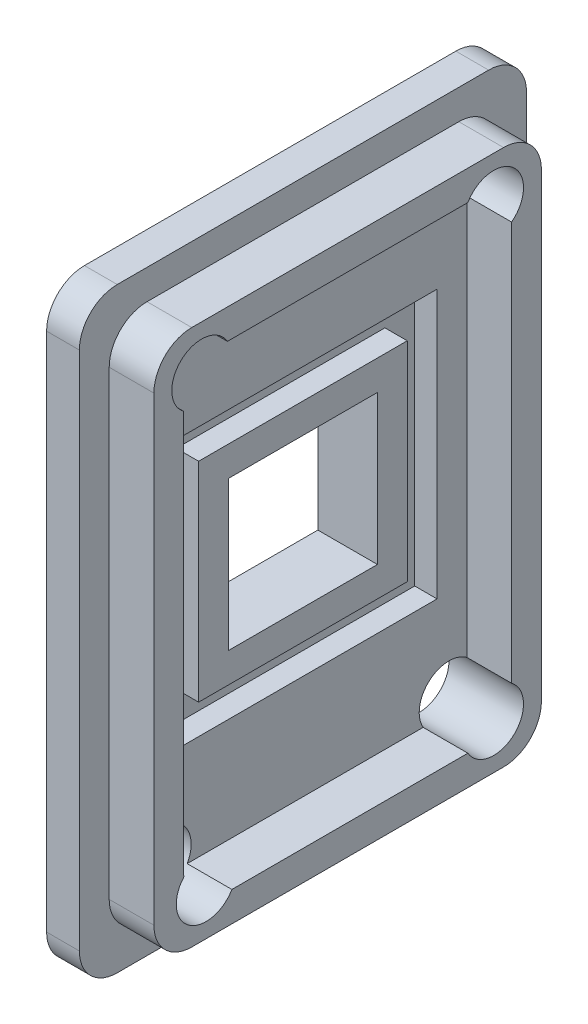
SolidWorks part; units mm, degrees
ref_plane "Front Plane" through (0, 0, 0) normal (0, 0, 1) x (1, 0, 0)
ref_plane "Top Plane" through (0, 0, 0) normal (0, 1, 0) x (1, 0, 0)
ref_plane "Right Plane" through (0, 0, 0) normal (1, 0, 0) x (0, 0, -1)
sketch "Sketch2" plane through (0, 0, 0) normal (1, 0, 0) x (0, 0, -1)
  line L1 (2.54, 0) -> (27.46, 0)
  line L2 (0, 2.54) -> (0, 37.46)
  line L3 (2.54, 40) -> (27.46, 40)
  line L4 (30, 2.54) -> (30, 37.46)
  arc A0 (2.54, 0) -> (0, 2.54) centre (2.54, 2.54) cw
  arc A1 (30, 2.54) -> (27.46, 0) centre (27.46, 2.54) cw
  arc A2 (30, 37.46) -> (27.46, 40) centre (27.46, 37.46) ccw
  arc A3 (2.54, 40) -> (0, 37.46) centre (2.54, 37.46) ccw
  point P7 (0, 0)
  point P12 (30, 40)
  point P15 (0, 40)
  dimension "D3" = 2.54
  dimension "D1" = 40
  dimension "D2" = 30
extrude "Boss-Extrude2" add sketch "Sketch2" along normal blind 2
sketch "Sketch3" plane through (0, 0, 0) normal (-1, 0, 0) x (0, 0, 1)
  line L0 (0, 37.46) -> (0, 2.54) construction
  line L1 (-18, 23) -> (-12, 23)
  line L2 (-18, 23) -> (-18, 17)
  line L3 (-18, 17) -> (-12, 17)
  line L4 (-12, 23) -> (-12, 17)
  line L5 (-27.46, 40) -> (-2.54, 40) construction
  dimension "D1" = 6
  dimension "D2" = 6
  dimension "D3" = 12
  dimension "D4" = 17
extrude "Cut-Extrude1" cut sketch "Sketch3" against normal blind 2
sketch "Sketch4" plane through (0, 0, 0) normal (-1, 0, 0) x (0, 0, 1)
  circle A0 centre (-15, 20) radius 5
  dimension "D1" = 10
extrude "Boss-Extrude3" add sketch "Sketch4" along normal blind 1.5
sketch "Sketch5" plane through (0, 0, 0) normal (-1, 0, 0) x (0, 0, 1)
  line L0 (-21, 26) -> (-9, 26)
  line L1 (-9, 26) -> (-9, 14)
  line L2 (-9, 14) -> (-21, 14)
  line L3 (-21, 14) -> (-21, 26)
  line L4 (-27.46, 40) -> (-2.54, 40) construction
  line L5 (0, 37.46) -> (0, 2.54) construction
  dimension "D1" = 12
  dimension "D2" = 12
  dimension "D3" = 14
  dimension "D4" = 9
extrude "Boss-Extrude4" add sketch "Sketch5" along normal blind 1
sketch "Sketch6" plane through (2, 0, 0) normal (1, 0, 0) x (0, 0, -1)
  line L0 (12, 23) -> (18, 23)
  line L1 (18, 23) -> (18, 17)
  line L2 (18, 17) -> (12, 17)
  line L3 (12, 17) -> (12, 23)
extrude "Cut-Extrude2" cut sketch "Sketch6" against normal blind 10
sketch "Sketch7" plane through (0, 0, 0) normal (-1, 0, 0) x (0, 0, 1)
  line L0 (-23, 28) -> (-7, 28)
  line L4 (-9, 26) -> (-21, 26) construction
  line L5 (-23, 28) -> (-23, 12)
  line L6 (-7, 28) -> (-7, 12)
  line L7 (-23, 12) -> (-7, 12)
  line L8 (-21, 14) -> (-9, 14) construction
  line L9 (-9, 14) -> (-9, 26) construction
  line L10 (-21, 26) -> (-21, 14) construction
  dimension "D1" = 2
  dimension "D2" = 2
  dimension "D3" = 2
  dimension "D4" = 2
extrude "Boss-Extrude5" add sketch "Sketch7" along normal blind 1
sketch "Sketch9" plane through (-1, 0, 0) normal (-1, 0, 0) x (0, 0, 1)
  circle A0 centre (-15, 20) radius 6
  dimension "D1" = 12
extrude "Boss-Extrude6" add sketch "Sketch9" along normal blind 1
sketch "Sketch10" plane through (0, 0, 0) normal (1, 0, 0) x (0, 0, -1)
  line L0 (12, 23) -> (18, 23)
  line L1 (18, 23) -> (18, 17)
  line L2 (18, 17) -> (12, 17)
  line L3 (12, 17) -> (12, 23)
extrude "Cut-Extrude3" cut sketch "Sketch10" against normal blind 10
sketch "Sketch11" plane through (2, 0, 0) normal (1, 0, 0) x (0, 0, -1)
  line L0 (4.54, 38) -> (25.46, 38)
  line L1 (28, 35.46) -> (28, 4.54)
  line L2 (25.46, 2) -> (4.54, 2)
  line L3 (2, 4.54) -> (2, 35.46)
  line L4 (27.46, 40) -> (2.54, 40) construction
  line L5 (0, 37.46) -> (0, 2.54) construction
  line L6 (6.54, 36) -> (23.46, 36)
  line L7 (26, 33.46) -> (26, 6.54)
  line L8 (23.46, 4) -> (6.54, 4)
  line L9 (4, 6.54) -> (4, 33.46)
  arc A0 (28, 4.54) -> (25.46, 2) centre (25.46, 4.54) cw
  arc A1 (25.46, 38) -> (28, 35.46) centre (25.46, 35.46) cw
  arc A2 (4.54, 38) -> (2, 35.46) centre (4.54, 35.46) ccw
  arc A3 (4.54, 2) -> (2, 4.54) centre (4.54, 4.54) cw
  arc A4 (4, 6.54) -> (6.54, 4) centre (6.54, 6.54) ccw
  arc A5 (26, 6.54) -> (23.46, 4) centre (23.46, 6.54) cw
  arc A6 (23.46, 36) -> (26, 33.46) centre (23.46, 33.46) cw
  arc A7 (6.54, 36) -> (4, 33.46) centre (6.54, 33.46) ccw
  point P10 (28, 2)
  point P13 (28, 38)
  point P16 (2, 38)
  dimension "D5" = 2.54
  dimension "D10" = 2.54
  dimension "D1" = 26
  dimension "D2" = 36
  dimension "D3" = 2
  dimension "D4" = 2
  dimension "D6" = 2
  dimension "D7" = 2
  dimension "D8" = 2
  dimension "D9" = 2
extrude "Boss-Extrude7" add sketch "Sketch11" along normal blind 3
sketch "Sketch12" plane through (-1, 0, 0) normal (-1, 0, 0) x (0, 0, 1)
  line L4 (-23, 28) -> (-20.46, 28)
  line L5 (-7, 28) -> (-7, 25.46)
  line L6 (-7, 12) -> (-9.54, 12)
  line L7 (-23, 12) -> (-23, 14.54)
  line L8 (-23, 25.46) -> (-23, 28)
  line L9 (-7, 14.54) -> (-7, 12)
  line L10 (-9.54, 28) -> (-7, 28)
  line L11 (-20.46, 12) -> (-23, 12)
  arc A0 (-9.54, 28) -> (-7, 25.46) centre (-9.54, 25.46) cw
  arc A1 (-7, 14.54) -> (-9.54, 12) centre (-9.54, 14.54) cw
  arc A2 (-23, 14.54) -> (-20.46, 12) centre (-20.46, 14.54) ccw
  arc A3 (-23, 25.46) -> (-20.46, 28) centre (-20.46, 25.46) cw
  point P10 (-7, 28)
  point P13 (-7, 12)
  point P16 (-23, 12)
  point P19 (-23, 28)
  dimension "D1" = 2.54
extrude "Cut-Extrude4" cut sketch "Sketch12" against normal blind 1
sketch "Sketch13" plane through (2, 0, 0) normal (1, 0, 0) x (0, 0, -1)
  line L0 (10, 25) -> (20, 25)
  line L1 (20, 25) -> (20, 15)
  line L2 (10, 25) -> (10, 15)
  line L3 (10, 15) -> (20, 15)
  line L4 (12, 23) -> (18, 23) construction
  line L5 (12, 17) -> (12, 23) construction
  line L6 (18, 17) -> (12, 17) construction
  line L7 (18, 23) -> (18, 17) construction
  line L8 (8, 27) -> (22, 27)
  line L9 (22, 27) -> (22, 13)
  line L10 (22, 13) -> (8, 13)
  line L11 (8, 13) -> (8, 27)
  dimension "D1" = 2
  dimension "D2" = 2
  dimension "D3" = 2
  dimension "D4" = 2
  dimension "D5" = 2
  dimension "D6" = 2
  dimension "D7" = 2
  dimension "D8" = 2
extrude "Cut-Extrude5" cut sketch "Sketch13" against normal blind 1.5
sketch "Sketch14" plane through (-2, 0, 0) normal (-1, 0, 0) x (0, 0, 1)
  line L0 (-12, 23) -> (-18, 23) construction
  line L1 (-17.46, 25) -> (-12.54, 25)
  line L2 (-20, 22.46) -> (-20, 17.54)
  line L3 (-17.46, 15) -> (-12.54, 15)
  line L4 (-10, 22.46) -> (-10, 17.54)
  line L6 (-18, 17) -> (-12, 17) construction
  line L7 (-18, 23) -> (-18, 17) construction
  line L8 (-12, 17) -> (-12, 23) construction
  arc A0 (-12.54, 15) -> (-10, 17.54) centre (-12.54, 17.54) ccw
  arc A1 (-10, 22.46) -> (-12.54, 25) centre (-12.54, 22.46) ccw
  arc A2 (-17.46, 25) -> (-20, 22.46) centre (-17.46, 22.46) ccw
  arc A3 (-17.46, 15) -> (-20, 17.54) centre (-17.46, 17.54) cw
  dimension "D5" = 2.54
  dimension "D1" = 2
  dimension "D2" = 2
  dimension "D3" = 2
  dimension "D4" = 2
extrude "Boss-Extrude8" add sketch "Sketch14" against normal blind 3
sketch "Sketch16" plane through (-2, 0, 0) normal (-1, 0, 0) x (0, 0, 1)
  circle A0 centre (-15, 20) radius 7
  arc A1 (-10.4796, 16.0546) -> (-10.4796, 23.9454) centre (-15, 20) ccw construction
  dimension "D1" = 1
extrude "Boss-Extrude9" add sketch "Sketch16" against normal blind 1
sketch "Sketch17" plane through (1, 0, 0) normal (1, 0, 0) x (0, 0, -1)
  line L0 (12, 23) -> (18, 23)
  line L1 (18, 23) -> (18, 17) construction
  line L2 (18, 17) -> (18, 23) construction
  line L3 (18, 23) -> (18, 17)
  line L4 (18, 17) -> (12, 17)
  line L5 (12, 17) -> (12, 23)
extrude "Cut-Extrude7" cut sketch "Sketch17" against normal blind 4
sketch "Sketch18" plane through (-2, 0, 0) normal (-1, 0, 0) x (0, 0, 1)
  line L0 (-19, 24) -> (-19, 16)
  line L1 (-19, 24) -> (-11, 24)
  line L2 (-12, 23) -> (-18, 23) construction
  line L3 (-18, 23) -> (-18, 17) construction
  line L4 (-19, 16) -> (-11, 16)
  line L5 (-11, 16) -> (-11, 24)
  dimension "D1" = 8
  dimension "D2" = 8
  dimension "D3" = 1
  dimension "D4" = 1
extrude "Cut-Extrude8" cut sketch "Sketch18" against normal blind 10
sketch "Sketch19" plane through (0.5, 0, 0) normal (1, 0, 0) x (0, 0, -1)
  line L0 (11, 24) -> (19, 24)
  line L1 (19, 24) -> (19, 16)
  line L2 (19, 16) -> (11, 16)
  line L3 (11, 16) -> (11, 24)
  line L5 (9, 26) -> (21, 26)
  line L6 (9, 26) -> (9, 14)
  line L7 (9, 14) -> (21, 14)
  line L8 (21, 26) -> (21, 14)
  point P12 (15, 14)
  dimension "D1" = 2
  dimension "D2" = 2
  dimension "D3" = 2
  dimension "D4" = 2
extrude "Boss-Extrude10" add sketch "Sketch19" along normal blind 1.5
sketch "Sketch20" plane through (2, 0, 0) normal (1, 0, 0) x (0, 0, -1)
  line L0 (7, 28) -> (23, 28)
  line L1 (9, 26) -> (21, 26)
  line L2 (9, 26) -> (9, 14)
  line L3 (9, 14) -> (21, 14)
  line L4 (21, 26) -> (21, 14)
  line L5 (23, 28) -> (23, 12)
  line L6 (23, 12) -> (7, 12)
  line L7 (7, 12) -> (7, 28)
  dimension "D1" = 2
  dimension "D2" = 2
  dimension "D3" = 2
  dimension "D4" = 2
extrude "Cut-Extrude9" cut sketch "Sketch20" against normal blind 1.5
sketch "Sketch23" plane through (2, 0, 0) normal (1, 0, 0) x (0, 0, -1)
  line L1 (10, 25) -> (20, 25)
  line L2 (10, 25) -> (10, 15)
  line L3 (10, 15) -> (20, 15)
  line L4 (20, 25) -> (20, 15)
  line L5 (11, 24) -> (19, 24)
  line L6 (11, 24) -> (11, 16)
  line L7 (11, 16) -> (19, 16)
  line L8 (19, 24) -> (19, 16)
  dimension "D1" = 1
  dimension "D2" = 1
  dimension "D3" = 1
  dimension "D4" = 1
extrude "Cut-Extrude15" cut sketch "Sketch23" against normal blind 10
sketch "Sketch24" plane through (-1, 0, 0) normal (-1, 0, 0) x (0, 0, 1)
  circle A0 centre (-15, 20) radius 8
extrude "Boss-Extrude11" add sketch "Sketch24" along normal blind 1
sketch "Sketch25" plane through (-1, 0, 0) normal (1, 0, 0) x (0, 0, -1)
  line L1 (10, 25) -> (20, 25)
  line L2 (10, 25) -> (10, 15)
  line L3 (10, 15) -> (20, 15)
  line L4 (20, 25) -> (20, 15)
extrude "Cut-Extrude16" cut sketch "Sketch25" against normal blind 1
sketch "Sketch26" plane through (0, 0, 0) normal (-1, 0, 0) x (0, 0, 1)
  line L0 (-23, 25.46) -> (-23, 20) construction
  line L1 (-21.46, 29) -> (-8.54, 29)
  line L2 (-24, 26.46) -> (-24, 13.54)
  line L3 (-21.46, 11) -> (-8.54, 11)
  line L4 (-6, 26.46) -> (-6, 13.54)
  line L5 (-9.54, 28) -> (-20.46, 28) construction
  line L6 (-7, 14.54) -> (-7, 25.46) construction
  line L7 (-20.46, 12) -> (-9.54, 12) construction
  arc A0 (-24, 13.54) -> (-21.46, 11) centre (-21.46, 13.54) ccw
  arc A1 (-6, 13.54) -> (-8.54, 11) centre (-8.54, 13.54) cw
  arc A2 (-8.54, 29) -> (-6, 26.46) centre (-8.54, 26.46) cw
  arc A3 (-21.46, 29) -> (-24, 26.46) centre (-21.46, 26.46) ccw
  dimension "D5" = 2.54
  dimension "D1" = 1
  dimension "D2" = 1
  dimension "D3" = 1
  dimension "D4" = 1
extrude "Boss-Extrude12" add sketch "Sketch26" along normal blind 1
sketch "Sketch27" plane through (0, 0, 0) normal (1, 0, 0) x (0, 0, -1)
  line L1 (10, 25) -> (20, 25)
  line L2 (10, 25) -> (10, 15)
  line L3 (10, 15) -> (20, 15)
  line L4 (20, 25) -> (20, 15)
extrude "Cut-Extrude17" cut sketch "Sketch27" against normal blind 1
sketch "Sketch28" plane through (0.5, 0, 0) normal (1, 0, 0) x (0, 0, -1)
  line L1 (9, 26) -> (21, 26)
  line L2 (9, 26) -> (9, 14)
  line L3 (9, 14) -> (21, 14)
  line L4 (21, 26) -> (21, 14)
  line L5 (8, 27) -> (22, 27)
  line L6 (8, 27) -> (8, 13)
  line L7 (8, 13) -> (22, 13)
  line L8 (22, 27) -> (22, 13)
  dimension "D1" = 1
  dimension "D2" = 1
  dimension "D3" = 1
  dimension "D4" = 1
extrude "Boss-Extrude13" add sketch "Sketch28" along normal blind 1.5
sketch "Sketch29" plane through (2, 0, 0) normal (1, 0, 0) x (0, 0, -1)
  line L1 (7, 28) -> (23, 28)
  line L2 (7, 28) -> (7, 12)
  line L3 (7, 12) -> (23, 12)
  line L4 (23, 28) -> (23, 12)
  line L5 (6, 29) -> (24, 29)
  line L6 (6, 29) -> (6, 11)
  line L7 (6, 11) -> (24, 11)
  line L8 (24, 29) -> (24, 11)
  dimension "D1" = 1
  dimension "D2" = 1
  dimension "D3" = 1
  dimension "D4" = 1
extrude "Cut-Extrude18" cut sketch "Sketch29" against normal blind 1.5
sketch "Sketch30" plane through (0, 0, 0) normal (-1, 0, 0) x (0, 0, 1)
  line L0 (-26.96, 39.5) -> (-3.04, 39.5)
  line L1 (-0.5, 36.96) -> (-0.5, 3.14)
  line L2 (-3.04, 0.6) -> (-26.96, 0.6)
  line L3 (-29.5, 3.14) -> (-29.5, 36.96)
  line L4 (-27.46, 40) -> (-2.54, 40) construction
  line L5 (-30, 2.54) -> (-30, 37.46) construction
  line L6 (-2.54, 0) -> (-27.46, 0) construction
  line L7 (0, 37.46) -> (0, 2.54) construction
  line L9 (-27.46, 40) -> (-2.54, 40)
  line L10 (-30, 37.46) -> (-30, 2.54)
  line L11 (-27.46, 0) -> (-2.54, 0)
  line L12 (0, 37.46) -> (0, 2.54)
  arc A0 (-26.96, 0.6) -> (-29.5, 3.14) centre (-26.96, 3.14) cw
  arc A1 (-0.5, 3.14) -> (-3.04, 0.6) centre (-3.04, 3.14) cw
  arc A2 (-0.5, 36.96) -> (-3.04, 39.5) centre (-3.04, 36.96) ccw
  arc A3 (-26.96, 39.5) -> (-29.5, 36.96) centre (-26.96, 36.96) ccw
  arc A4 (-30, 2.54) -> (-27.46, 0) centre (-27.46, 2.54) ccw
  arc A5 (-2.54, 0) -> (0, 2.54) centre (-2.54, 2.54) ccw
  arc A6 (0, 37.46) -> (-2.54, 40) centre (-2.54, 37.46) ccw
  arc A7 (-27.46, 40) -> (-30, 37.46) centre (-27.46, 37.46) ccw
  point P29 (0, 0)
  dimension "D5" = 2.54
  dimension "D6" = 2.54
  dimension "D1" = 0.5
  dimension "D2" = 0.5
  dimension "D3" = 0.6
  dimension "D4" = 0.5
extrude "Boss-Extrude14" add sketch "Sketch30" along normal blind 0.2
sketch "Sketch31" plane through (2, 0, 0) normal (1, 0, 0) x (0, 0, -1)
  line L6 (15, -3.6231) -> (15, 43.2498) construction
  line L7 (-4.8575, 19.8133) -> (35.308, 19.8133) construction
  circle A6 centre (5.2, 35) radius 2
  circle A7 centre (24.8, 35) radius 2
  circle A8 centre (24.8, 5) radius 2
  circle A9 centre (5.5, 5) radius 2
  dimension "D8" = 4
  dimension "D9" = 4
  dimension "D10" = 4
  dimension "D11" = 4
extrude "Cut-Extrude19" cut sketch "Sketch31" against normal mid plane 15.652
